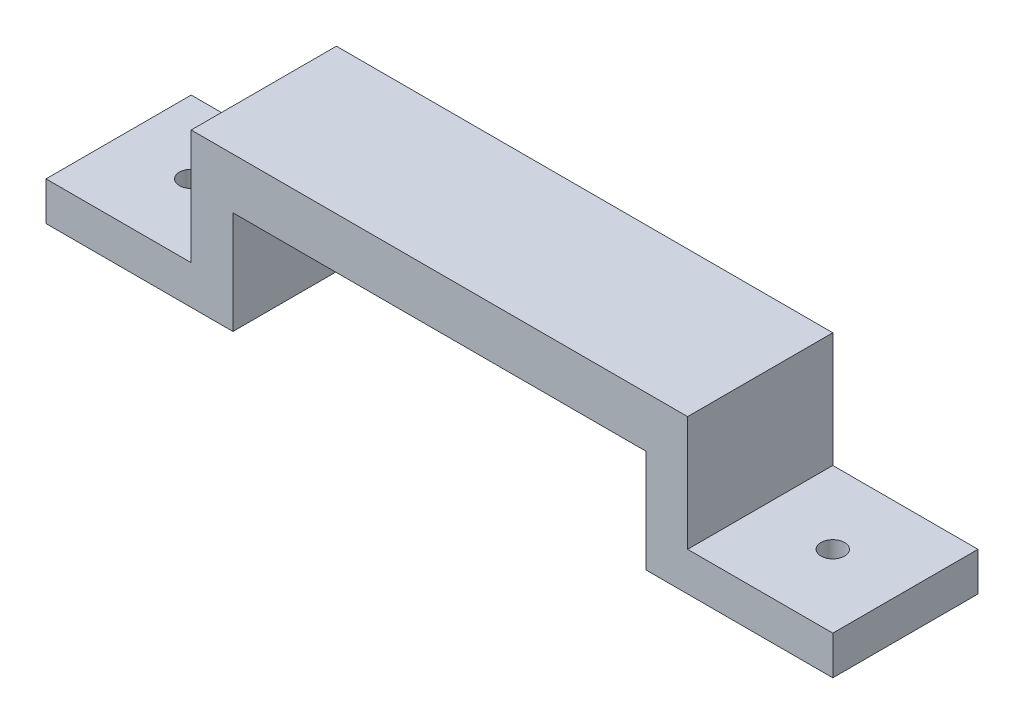
SolidWorks part; units mm, degrees
ref_plane "前视基准面" through (0, 0, 0) normal (0, 0, 1) x (1, 0, 0)
ref_plane "上视基准面" through (0, 0, 0) normal (0, 1, 0) x (1, 0, 0)
ref_plane "右视基准面" through (0, 0, 0) normal (1, 0, 0) x (0, 0, -1)
sketch "草图2" plane through (0, 0, 0) normal (0, 0, 1) x (1, 0, 0)
  line L1 (-20.1082, 12.6633) -> (34.5918, 12.6633)
  line L2 (-20.1082, 12.6633) -> (-20.1082, -4.2667)
  line L3 (-20.1082, -4.2667) -> (34.5918, -4.2667)
  line L4 (34.5918, 12.6633) -> (34.5918, -4.2667)
  line L5 (-15.5082, 8.0633) -> (29.9918, 8.0633)
  line L6 (-15.5082, 8.0633) -> (-15.5082, -4.2667)
  line L7 (-15.5082, -4.2667) -> (29.9918, -4.2667)
  line L8 (29.9918, 8.0633) -> (29.9918, -4.2667)
  dimension "D1" = 54.7
  dimension "D2" = 16.93
  dimension "D3" = 4.6
  dimension "D4" = 45.5
  dimension "D5" = 4.6
  dimension "D6" = 4.6
extrude "凸台-拉伸1" add sketch "草图2" along normal blind 16 contours L5 L8 L3 L4 L1 L2 L6
sketch "草图3" plane through (-20.1082, 0, 0) normal (-1, 0, 0) x (0, 0, 1)
  line L0 (16, -4.2667) -> (0, -4.2667) construction
  line L3 (0, -4.2667) -> (8, -4.2667)
  line L9 (0, 0) -> (16, 0)
  line L10 (0, 0) -> (0, -4.2667)
  line L11 (0, -4.2667) -> (16, -4.2667)
  line L12 (16, 0) -> (16, -4.2667)
  dimension "D1" = 4.2667
sketch "草图5" plane through (-20.1082, 0, 0) normal (-1, 0, 0) x (0, 0, 1)
extrude "凸台-拉伸3" add sketch "草图3" along normal blind 16 contours L10 L9 L12 L11
sketch "草图17" plane through (0, 0, 0) normal (0, 1, 0) x (1, 0, 0)
  point P0 (-27.8685, -8.0352)
  point P2 (-27.8685, -8.0352)
sketch "草图22" plane through (0, 0, 0) normal (0, 1, 0) x (1, 0, 0)
sketch "草图23" plane through (34.5918, 0, 0) normal (1, 0, 0) x (0, 0, -1)
  line L1 (0, 0) -> (-16, 0)
  line L2 (0, 0) -> (0, -4.2667)
  line L3 (0, -4.2667) -> (-16, -4.2667)
  line L4 (-16, 0) -> (-16, -4.2667)
  dimension "D1" = 4.2667
extrude "凸台-拉伸4" add sketch "草图23" along normal blind 16
sketch "草图24" plane through (0, 0, 0) normal (0, 1, 0) x (1, 0, 0)
  line L0 (34.5918, 0) -> (50.5918, -16) construction
  line L1 (50.5918, -16) -> (50.5918, 0) construction
  line L2 (50.5918, 0) -> (34.5918, -16) construction
  point P13 (42.5918, -8)
hole_wizard "Ø2.0mm 暗销孔2" positions "草图24" profile "草图25" hole size "Ø2.0" standard "GB" end condition through all
sketch "草图25" plane through (42.5918, 0, 8) normal (1, 0, 0) x (0, 0, 1)
  line L0 (0, 0) -> (0, 4.2667)
  line L1 (0, 4.2667) -> (1.3, 4.2667)
  line L2 (1.3, 4.2667) -> (1.3, 0)
  line L5 (1.3, 0) -> (0, 0)
  line L11 (0, -6.35) -> (0, 107.95) construction
  dimension "通孔孔直径" = 2.6
  dimension "通孔孔深度" = 4.2667
sketch "草图28" plane through (0, 0, 16) normal (0, 0, 1) x (1, 0, 0)
sketch "草图29" plane through (0, 0, 16) normal (0, 0, 1) x (1, 0, 0)
sketch "草图30" plane through (0, 0, 0) normal (0, 1, 0) x (1, 0, 0)
  line L0 (-36.1082, 0) -> (-20.1082, -16) construction
  line L2 (-20.1082, 0) -> (-36.1082, -16) construction
sketch "草图31" plane through (0, 0, 0) normal (0, 1, 0) x (1, 0, 0)
  line L0 (-36.1082, 0) -> (-20.1082, -16) construction
  point P0 (-28.1082, -8)
hole_wizard "Ø2.0mm 暗销孔3" positions "草图31" profile "草图32" hole size "Ø2.0" standard "BSI" end condition through all
sketch "草图32" plane through (-28.1082, 0, 8) normal (1, 0, 0) x (0, 0, 1)
  line L0 (0, 0) -> (0, 4.2667)
  line L1 (0, 4.2667) -> (1.3, 4.2667)
  line L2 (1.3, 4.2667) -> (1.3, 0)
  line L5 (1.3, 0) -> (0, 0)
  line L11 (0, -6.35) -> (0, 107.95) construction
  dimension "通孔孔直径" = 2.6
  dimension "通孔孔深度" = 4.2667
sketch "草图33" plane through (0, 8.0633, 0) normal (0, -1, 0) x (1, 0, 0)
  line L1 (-15.5082, 16) -> (29.9918, 16)
  line L2 (-15.5082, 16) -> (-15.5082, 0)
  line L3 (-15.5082, 0) -> (29.9918, 0)
  line L4 (29.9918, 16) -> (29.9918, 0)
extrude "凸台-拉伸5" add sketch "草图33" along normal blind 1
